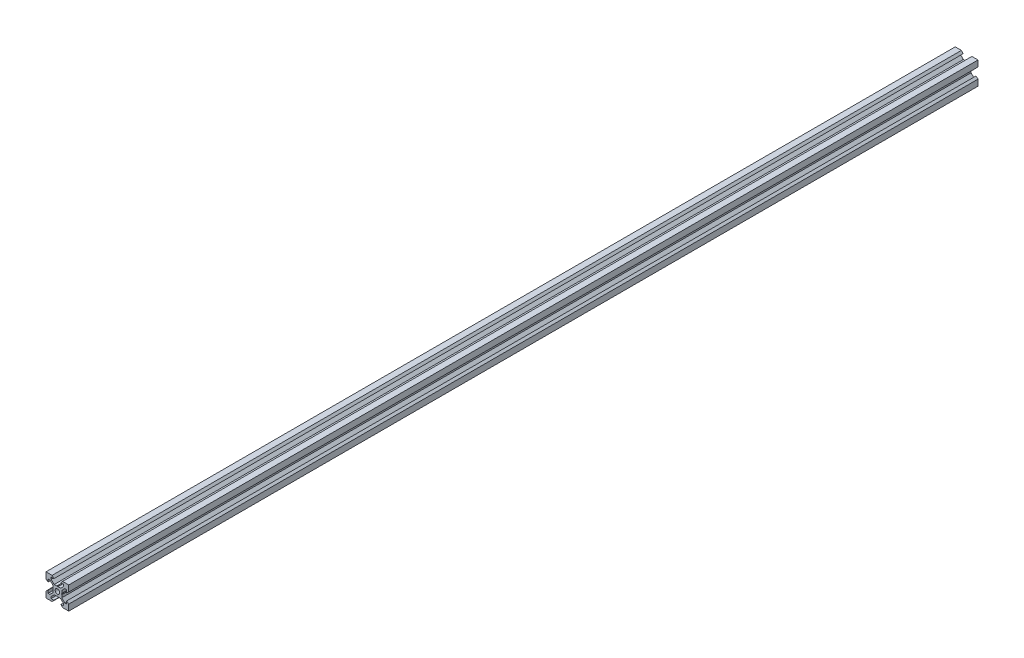
SolidWorks part; units mm, degrees
ref_plane "Front Plane" through (0, 0, 0) normal (0, 0, 1) x (1, 0, 0)
ref_plane "Top Plane" through (0, 0, 0) normal (0, 1, 0) x (1, 0, 0)
ref_plane "Right Plane" through (0, 0, 0) normal (1, 0, 0) x (0, 0, -1)
sketch "Sketch1" plane through (0, 0, 0) normal (0, 0, 1) x (1, 0, 0)
  line L0 (10, 10) -> (4.6104, 10) construction
  line L1 (10, 10) -> (10, 4.6104) construction
  line L2 (10, -10) -> (10, -4.6104) construction
  line L3 (10, -10) -> (4.6104, -10) construction
  line L4 (10, 10) -> (10, 4.6104)
  line L5 (6.5607, 5.5) -> (8.2, 5.5)
  line L6 (5.5, 8.2) -> (5.5, 6.5607)
  line L7 (10, 10) -> (4.6104, 10)
  line L8 (10, 10) -> (10, 4.6104)
  line L9 (6.5607, 5.5) -> (3.9, 2.8393)
  line L10 (5.5, 6.5607) -> (2.8393, 3.9)
  line L11 (10, 4.6104) -> (8.2, 3.1)
  line L12 (4.6104, 10) -> (3.1, 8.2)
  line L13 (8.2, 3.1) -> (8.2, 5.5)
  line L14 (3.1, 8.2) -> (5.5, 8.2)
  line L15 (-6.5607, 5.5) -> (-8.2, 5.5)
  line L16 (6.5607, -5.5) -> (8.2, -5.5)
  line L17 (3.1, -8.2) -> (5.5, -8.2)
  line L18 (8.2, -3.1) -> (8.2, -5.5)
  line L19 (4.6104, -10) -> (3.1, -8.2)
  line L20 (10, -4.6104) -> (8.2, -3.1)
  line L21 (0.5196, -3.9) -> (0, -3.6)
  line L22 (0.5196, 3.9) -> (0, 3.6)
  line L23 (3.6, 0) -> (3.9, -0.5196)
  line L24 (3.9, 0.5196) -> (3.6, 0)
  line L25 (3.9, 0.5196) -> (3.9, 2.8393)
  line L26 (2.8393, 3.9) -> (0.5196, 3.9)
  line L27 (3.9, -2.8393) -> (3.9, -0.5196)
  line L28 (2.8393, -3.9) -> (0.5196, -3.9)
  line L29 (5.5, -6.5607) -> (2.8393, -3.9)
  line L30 (6.5607, -5.5) -> (3.9, -2.8393)
  line L31 (10, -10) -> (10, -4.6104)
  line L32 (10, -10) -> (4.6104, -10)
  line L33 (5.5, -8.2) -> (5.5, -6.5607)
  line L34 (-6.5607, -5.5) -> (-8.2, -5.5)
  line L35 (10, -10) -> (10, -4.6104)
  line L36 (0, 0) -> (0, 8.2) construction
  line L37 (-10, -10) -> (-4.6104, -10) construction
  line L38 (-10, -10) -> (-10, -4.6104) construction
  line L39 (-10, 10) -> (-10, 4.6104) construction
  line L40 (-10, 10) -> (-4.6104, 10) construction
  line L41 (-10, -10) -> (-10, -4.6104)
  line L43 (-5.5, -8.2) -> (-5.5, -6.5607)
  line L44 (-10, -10) -> (-4.6104, -10)
  line L45 (-10, -10) -> (-10, -4.6104)
  line L46 (-6.5607, -5.5) -> (-3.9, -2.8393)
  line L47 (-5.5, -6.5607) -> (-2.8393, -3.9)
  line L48 (-2.8393, -3.9) -> (-0.5196, -3.9)
  line L49 (-3.9, -2.8393) -> (-3.9, -0.5196)
  line L50 (-2.8393, 3.9) -> (-0.5196, 3.9)
  line L51 (-3.9, 0.5196) -> (-3.9, 2.8393)
  line L52 (-3.9, 0.5196) -> (-3.6, 0)
  line L53 (-3.6, 0) -> (-3.9, -0.5196)
  line L54 (-0.5196, 3.9) -> (0, 3.6)
  line L55 (-0.5196, -3.9) -> (0, -3.6)
  line L56 (-10, -4.6104) -> (-8.2, -3.1)
  line L57 (-4.6104, -10) -> (-3.1, -8.2)
  line L58 (-8.2, -3.1) -> (-8.2, -5.5)
  line L59 (-3.1, -8.2) -> (-5.5, -8.2)
  line L60 (-10, -10) -> (10, -10) construction
  line L61 (-10, -10) -> (-10, 10) construction
  line L62 (-3.1, 8.2) -> (-5.5, 8.2)
  line L63 (-8.2, 3.1) -> (-8.2, 5.5)
  line L64 (-4.6104, 10) -> (-3.1, 8.2)
  line L65 (-10, 4.6104) -> (-8.2, 3.1)
  line L66 (-5.5, 6.5607) -> (-2.8393, 3.9)
  line L67 (-6.5607, 5.5) -> (-3.9, 2.8393)
  line L68 (-10, 10) -> (-10, 4.6104)
  line L69 (-10, 10) -> (-4.6104, 10)
  line L70 (-5.5, 8.2) -> (-5.5, 6.5607)
  line L71 (-10, 10) -> (10, 10) construction
  line L72 (-10, 10) -> (-10, 4.6104)
  line L73 (10, -10) -> (10, 10) construction
  line L74 (-10, -10) -> (10, 10) construction
  line L75 (-10, 10) -> (10, -10) construction
  circle A0 centre (0, 0) radius 2
  dimension "D7" = 4
  dimension "D1" = 20
  dimension "D2" = 5.3896
  dimension "D3" = 4.5
  dimension "D4" = 50
  dimension "D5" = 1.8
  dimension "D6" = 1.5104
  dimension "D8" = 5.5
  dimension "D9" = 120
  dimension "D10" = 0.3
  dimension "D11" = 2.3197
  dimension "D12" = 7.8
  dimension "D13" = 7.8
  dimension "D14" = 1.5
  dimension "D15" = 2.6607
extrude "Boss-Extrude1" add sketch "Sketch1" along normal mid plane 800 contours L70 L62 L64 L69 L68 L65 L63 L15 L67 L51 L52 L53 L49 L46 L34 L58 L56 L41 L44 L57 L59 L43 L47 L48 L55 L21 L28 L29 L33 L17 L19 L32 L31 L20 L18 L16 L30 L27 L23 L24 L25 L9 L5 L13 L11 L4 L7 L12 L14 L6 L10
